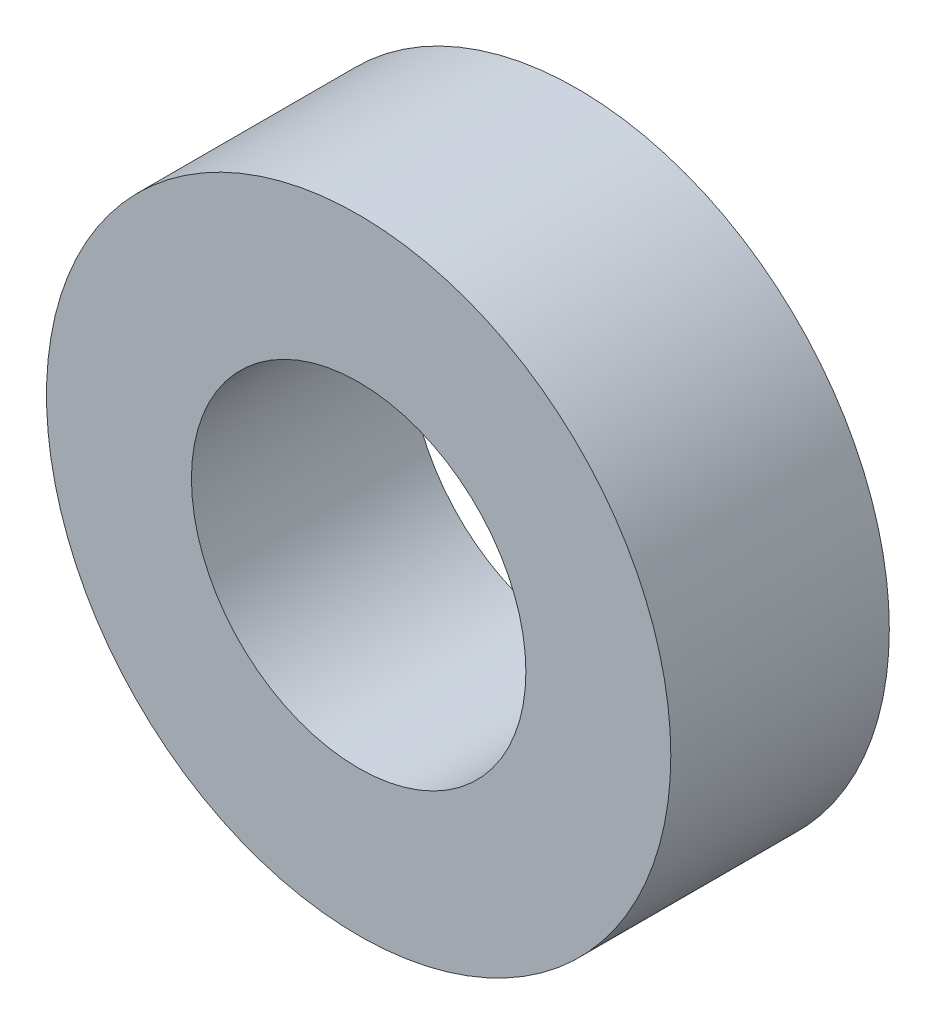
SolidWorks part; units mm, degrees
material "PET"
ref_plane "Front Plane" through (0, 0, 0) normal (0, 0, 1) x (1, 0, 0)
ref_plane "Top Plane" through (0, 0, 0) normal (0, 1, 0) x (1, 0, 0)
ref_plane "Right Plane" through (0, 0, 0) normal (1, 0, 0) x (0, 0, -1)
sketch "Sketch1" plane through (0, 0, 0) normal (0, 0, 1) x (1, 0, 0)
  circle A0 centre (0, 0) radius 4.7625
  circle A1 centre (0, 0) radius 8.89
  dimension "D1" = 17.78
  dimension "D2" = 9.525
extrude "Boss-Extrude1" add sketch "Sketch1" along normal mid plane 6.223
